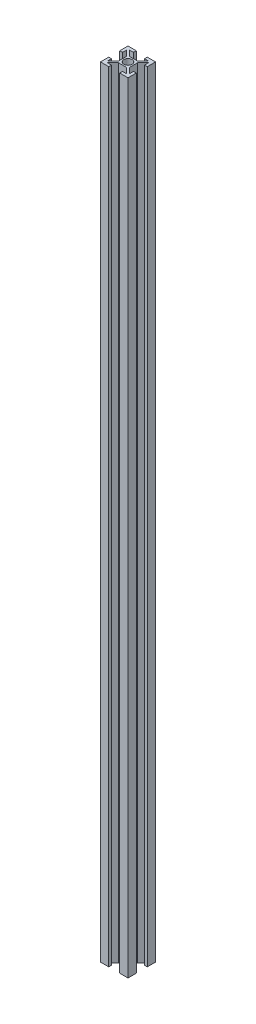
SolidWorks part; units mm, degrees
material "1060 Alloy"
ref_plane "Front Plane" through (0, 0, 0) normal (0, 0, 1) x (1, 0, 0)
ref_plane "Top Plane" through (0, 0, 0) normal (0, 1, 0) x (1, 0, 0)
ref_plane "Right Plane" through (0, 0, 0) normal (1, 0, 0) x (0, 0, -1)
sketch "Sketch1" plane through (0, 0, 0) normal (0, 0, 1) x (1, 0, 0)
  line L0 (18.2498, -12.1687) -> (272.6493, 146.831) construction
  line L1 (272.6493, 146.831) -> (18.2498, 553.8702) construction
  dimension "D1" = 300
  dimension "D2" = 480
  dimension "D3" = 90
sketch "2020 sketch" plane through (0, 0, 0) normal (0, 1, 0) x (1, 0, 0)
  line L0 (-4, 10) -> (-4, 8)
  line L1 (-10, 10) -> (-4, 10)
  line L2 (-10, 10) -> (-10, 4)
  line L3 (-10, -10) -> (-4, -10)
  line L4 (10, 10) -> (10, 4)
  line L5 (-10, 10) -> (10, -10) construction
  line L6 (-10, -10) -> (10, 10) construction
  line L7 (-4, 8) -> (-7, 8)
  line L8 (-7, 8) -> (-3, 4)
  line L9 (-3, 4) -> (3, 4)
  line L10 (3, 4) -> (7, 8)
  line L11 (7, 8) -> (4, 8)
  line L12 (4, 8) -> (4, 10)
  line L13 (4, 3) -> (4, -3)
  line L14 (8, 7) -> (4, 3)
  line L15 (8, 4) -> (8, 7)
  line L16 (10, 4) -> (8, 4)
  line L17 (8, -4) -> (10, -4)
  line L18 (8, -7) -> (8, -4)
  line L19 (4, -3) -> (8, -7)
  line L20 (3, -4) -> (-3, -4)
  line L21 (7, -8) -> (3, -4)
  line L22 (4, -8) -> (7, -8)
  line L23 (4, -10) -> (4, -8)
  line L24 (-4, -8) -> (-4, -10)
  line L25 (-7, -8) -> (-4, -8)
  line L26 (-3, -4) -> (-7, -8)
  line L27 (-4, -3) -> (-4, 3)
  line L28 (-8, -7) -> (-4, -3)
  line L29 (-8, -4) -> (-8, -7)
  line L30 (-10, -4) -> (-8, -4)
  line L31 (-8, 4) -> (-10, 4)
  line L32 (-8, 7) -> (-8, 4)
  line L33 (-4, 3) -> (-8, 7)
  line L34 (-10, -4) -> (-10, -10)
  line L35 (10, -4) -> (10, -10)
  line L36 (4, 10) -> (10, 10)
  line L37 (4, -10) -> (10, -10)
  circle A0 centre (0, 0) radius 3
  point P0 (0, 0)
  point P14 (4, 9)
  point P42 (0, 0)
  dimension "D9" = 6
  dimension "D1" = 20
  dimension "D2" = 20
  dimension "D3" = 8
  dimension "D4" = 6
  dimension "D5" = 6
  dimension "D6" = 2
  dimension "D7" = 4
  dimension "D8" = 4
extrude "Boss-Extrude1" add sketch "2020 sketch" along normal up to vertex (553.8702 mm away) from vertex at -12.1687 contours A0 | L28 L27 L33 L32 L31 L2 L1 L0 L7 L8 L9 L10 L11 L12 L36 L4 L16 L15 L14 L13 L19 L18 L17 L35 L37 L23 L22 L21 L20 L26 L25 L24 L3 L34 L30 L29
